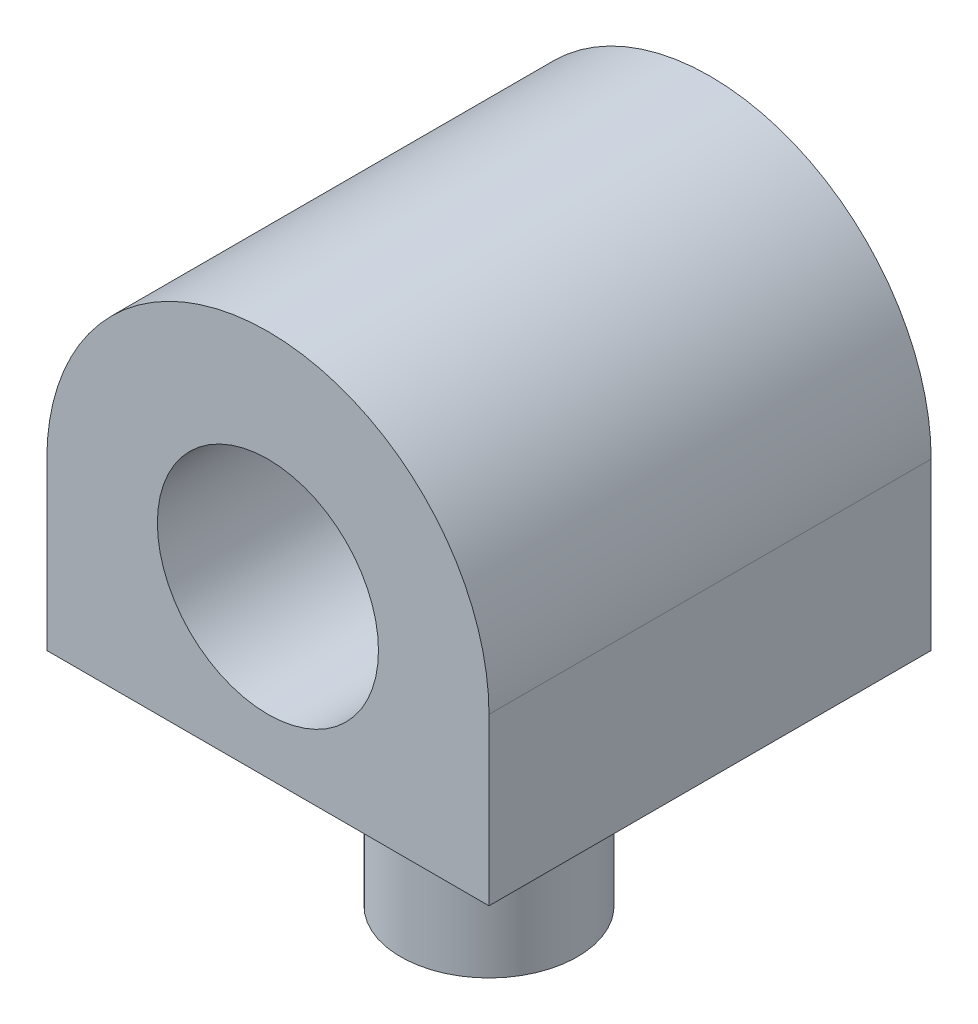
SolidWorks part; units mm, degrees
material "ABS"
ref_plane "正面" through (0, 0, 0) normal (0, 0, 1) x (1, 0, 0)
ref_plane "平面" through (0, 0, 0) normal (0, 1, 0) x (1, 0, 0)
ref_plane "右側面" through (0, 0, 0) normal (1, 0, 0) x (0, 0, -1)
sketch "ｽｹｯﾁ2" plane through (0, 0, 0) normal (0, 0, 1) x (1, 0, 0)
  line L0 (-10, 0) -> (-10, -7.5)
  line L1 (-10, -7.5) -> (10, -7.5)
  line L2 (10, -7.5) -> (10, 0)
  arc A0 (-10, 0) -> (10, 0) centre (0, 0) cw
  dimension "D1" = 10
  dimension "D2" = 7.5
extrude "ﾎﾞｽ - 押し出し1" add sketch "ｽｹｯﾁ2" along normal blind 20
sketch "ｽｹｯﾁ3" plane through (0, 0, 20) normal (0, 0, 1) x (1, 0, 0)
  circle A0 centre (0, 0) radius 5
  dimension "D1" = 10
extrude "ｶｯﾄ - 押し出し1" cut sketch "ｽｹｯﾁ3" against normal through all
sketch "ｽｹｯﾁ4" plane through (0, -7.5, 0) normal (0, -1, 0) x (1, 0, 0)
  line L1 (-10, 20) -> (10, 0) construction
  point P2 (0, 10)
  point P5 (-10, 20)
  point P8 (-10, 0)
sketch "ｽｹｯﾁ5" plane through (0, -7.5, 0) normal (0, -1, 0) x (-1, 0, 0)
  line L0 (10, -20) -> (-10, 0) construction
  circle A0 centre (0, -10) radius 4
  dimension "D1" = 8
extrude "ﾎﾞｽ - 押し出し2" add sketch "ｽｹｯﾁ5" along normal blind 10
sketch "ｽｹｯﾁ6" plane through (0, 0, 0) normal (0, 1, 0) x (1, 0, 0)
  line L0 (0, 0) -> (0, -20) construction
  line L1 (-10, -20) -> (10, -20) construction
  point P5 (0, -10)
